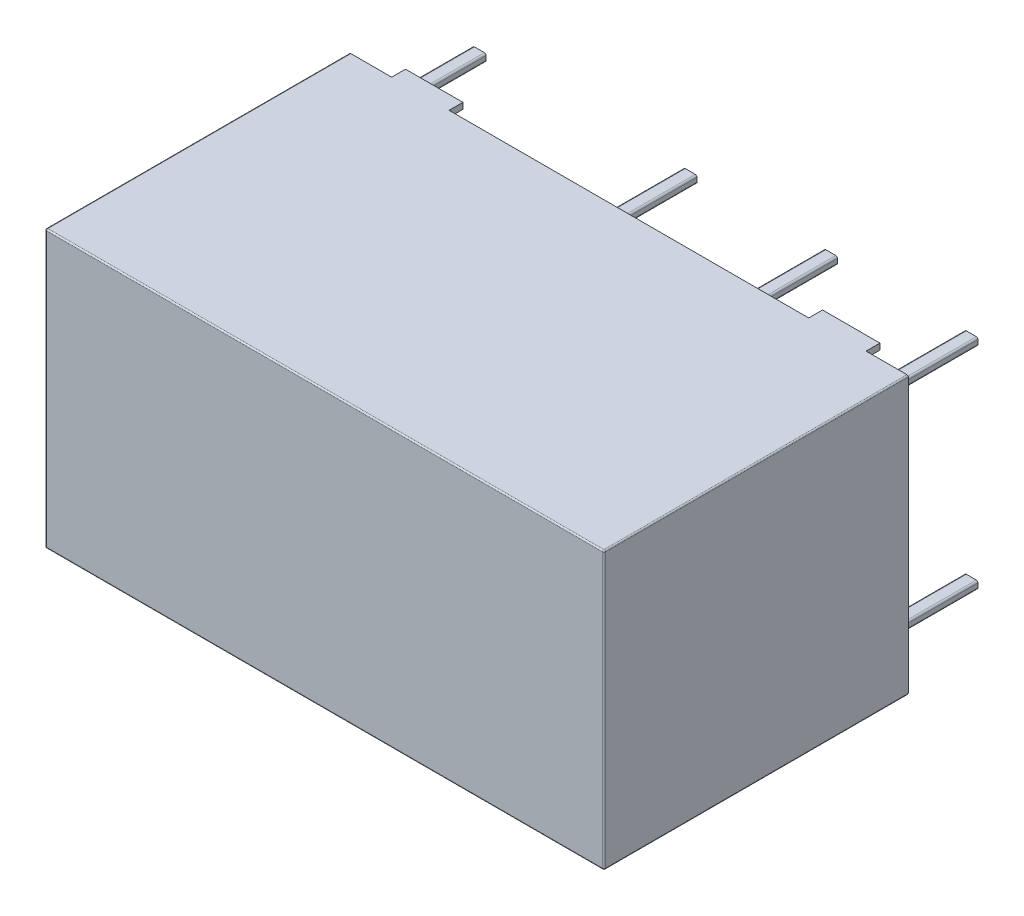
SolidWorks part; units mm, degrees
ref_plane "Front Plane" through (0, 0, 0) normal (0, 0, 1) x (1, 0, 0)
ref_plane "Top Plane" through (0, 0, 0) normal (0, 1, 0) x (1, 0, 0)
ref_plane "Right Plane" through (0, 0, 0) normal (1, 0, 0) x (0, 0, -1)
sketch "Sketch1" plane through (0, 0, 0) normal (0, 0, 1) x (1, 0, 0)
  line L1 (-10.1, 5) -> (10.1, 5)
  line L2 (-10.1, 5) -> (-10.1, -5)
  line L3 (-10.1, -5) -> (10.1, -5)
  line L4 (10.1, 5) -> (10.1, -5)
  line L5 (-10.1, 5) -> (10.1, -5) construction
  line L6 (-10.1, -5) -> (10.1, 5) construction
  point P0 (0, 0)
  dimension "D1" = 20.2
  dimension "D2" = 10
extrude "Boss-Extrude1" add sketch "Sketch1" along normal blind 11.5
sketch "Sketch2" plane through (0, 0, 0) normal (0, 0, -1) x (-1, 0, 0)
  line L0 (10.1, -5) -> (-10.1, -5) construction
  line L1 (6.5, -5) -> (-6.5, -5)
  line L2 (6.5, -5) -> (6.5, 5)
  line L3 (6.5, 5) -> (-6.5, 5)
  line L4 (-6.5, -5) -> (-6.5, 5)
  line L5 (6.5, -5) -> (-6.5, 5) construction
  line L6 (6.5, 5) -> (-6.5, -5) construction
  line L7 (-10.1, 5) -> (10.1, 5) construction
  line L9 (-10.1, -5) -> (-8.575, -5)
  line L10 (-10.1, -5) -> (-10.1, 5)
  line L11 (-10.1, 5) -> (-8.575, 5)
  line L12 (-8.575, -5) -> (-8.575, 5)
  line L13 (-10.1, -5) -> (-8.575, 5) construction
  line L14 (-10.1, 5) -> (-8.575, -5) construction
  line L15 (10.1, -5) -> (8.575, -5)
  line L16 (10.1, -5) -> (10.1, 5)
  line L17 (10.1, 5) -> (8.575, 5)
  line L18 (8.575, -5) -> (8.575, 5)
  line L19 (10.1, -5) -> (8.575, 5) construction
  line L20 (10.1, 5) -> (8.575, -5) construction
  point P4 (0, 0)
  point P13 (-9.3375, 0)
  point P19 (9.3375, 0)
  dimension "D1" = 17.15
  dimension "D2" = 13
extrude "Cut-Extrude1" cut sketch "Sketch2" against normal blind 0.5
sketch "Sketch3" plane through (0, 0, 0) normal (0, 0, -1) x (-1, 0, 0)
  line L0 (-8.575, -5) -> (-8.575, 5) construction
  line L1 (8.575, -4.78) -> (-8.575, -4.78)
  line L2 (8.575, -4.78) -> (8.575, 4.78)
  line L3 (8.575, 4.78) -> (-8.575, 4.78)
  line L4 (-8.575, -4.78) -> (-8.575, 4.78)
  line L5 (8.575, -4.78) -> (-8.575, 4.78) construction
  line L6 (8.575, 4.78) -> (-8.575, -4.78) construction
  line L7 (6.5, 5) -> (8.575, 5) construction
  point P0 (0, 0)
  dimension "D1" = 0.22
extrude "Cut-Extrude2" cut sketch "Sketch3" against normal up to surface (0.5 mm away) contours L2 L1 L4 L3 up to face at (0, 0, 0.5)
sketch "Sketch4" plane through (0, 0, 0.5) normal (0, 0, -1) x (-1, 0, 0)
  line L0 (10.1, -5) -> (10.1, 5) construction
  line L3 (9.14, -3.945) -> (8.66, -3.945)
  line L4 (9.14, -3.945) -> (9.14, -3.675)
  line L5 (9.14, -3.675) -> (8.66, -3.675)
  line L6 (8.66, -3.945) -> (8.66, -3.675)
  line L7 (9.14, -3.945) -> (8.66, -3.675) construction
  line L8 (9.14, -3.675) -> (8.66, -3.945) construction
  line L10 (6.6, -3.945) -> (6.12, -3.945)
  line L11 (6.6, -3.945) -> (6.6, -3.675)
  line L12 (6.6, -3.675) -> (6.12, -3.675)
  line L13 (6.12, -3.945) -> (6.12, -3.675)
  line L14 (6.6, -3.945) -> (6.12, -3.675) construction
  line L15 (6.6, -3.675) -> (6.12, -3.945) construction
  line L16 (1.52, -3.945) -> (1.04, -3.945)
  line L17 (1.52, -3.945) -> (1.52, -3.675)
  line L18 (1.52, -3.675) -> (1.04, -3.675)
  line L19 (1.04, -3.945) -> (1.04, -3.675)
  line L20 (1.52, -3.945) -> (1.04, -3.675) construction
  line L21 (1.52, -3.675) -> (1.04, -3.945) construction
  line L22 (-3.56, -3.945) -> (-4.04, -3.945)
  line L23 (-3.56, -3.945) -> (-3.56, -3.675)
  line L24 (-3.56, -3.675) -> (-4.04, -3.675)
  line L25 (-4.04, -3.945) -> (-4.04, -3.675)
  line L26 (-3.56, -3.945) -> (-4.04, -3.675) construction
  line L27 (-3.56, -3.675) -> (-4.04, -3.945) construction
  line L28 (-8.64, -3.945) -> (-9.12, -3.945)
  line L29 (-8.64, -3.945) -> (-8.64, -3.675)
  line L30 (-8.64, -3.675) -> (-9.12, -3.675)
  line L31 (-9.12, -3.945) -> (-9.12, -3.675)
  line L32 (-8.64, -3.945) -> (-9.12, -3.675) construction
  line L33 (-8.64, -3.675) -> (-9.12, -3.945) construction
  point P4 (8.9, -3.81)
  point P7 (6.36, -3.81)
  point P12 (1.28, -3.81)
  point P17 (-3.8, -3.81)
  point P22 (-8.88, -3.81)
  dimension "D7" = 5.08
  dimension "D1" = 0.48
  dimension "D2" = 0.27
  dimension "D3" = 3.81
  dimension "D4" = 1.2
  dimension "D5" = 2.54
  dimension "D6" = 5.08
  dimension "D8" = 5.08
extrude "Boss-Extrude2" add sketch "Sketch4" along normal offset from surface (3.5 mm away) 3 contours L6 L3 L4 L5 | L19 L16 L17 L18 | L25 L22 L23 L24 | L31 L28 L29 L30 up to face at (-7.5375, -4.89, 0) offset beyond the face yes
fillet "Fillet1" radius 0.06 16 edges at (-8.66, -3.675, -1.25) (-9.14, -3.675, -1.25) (-8.66, -3.945, -1.25) (-9.14, -3.945, -1.25) (8.64, -3.945, -1.25) (4.04, -3.675, -1.25) (-1.04, -3.675, -1.25) (8.64, -3.675, -1.25) (9.12, -3.945, -1.25) (9.12, -3.675, -1.25) (4.04, -3.945, -1.25) (-1.04, -3.945, -1.25) (-1.52, -3.675, -1.25) (3.56, -3.675, -1.25) (3.56, -3.945, -1.25) (-1.52, -3.945, -1.25)
mirror "Mirror1" about plane through (0, 0, 0) normal (0, 1, 0) of "Fillet1", "Boss-Extrude2"
fillet "Fillet2" radius 0.05 8 edges at (10.1, 5, 6) (10.1, 0, 11.5) (0, 5, 11.5) (-10.1, 5, 6) (10.1, -5, 6) (-10.1, 0, 11.5) (0, -5, 11.5) (-10.1, -5, 6)
